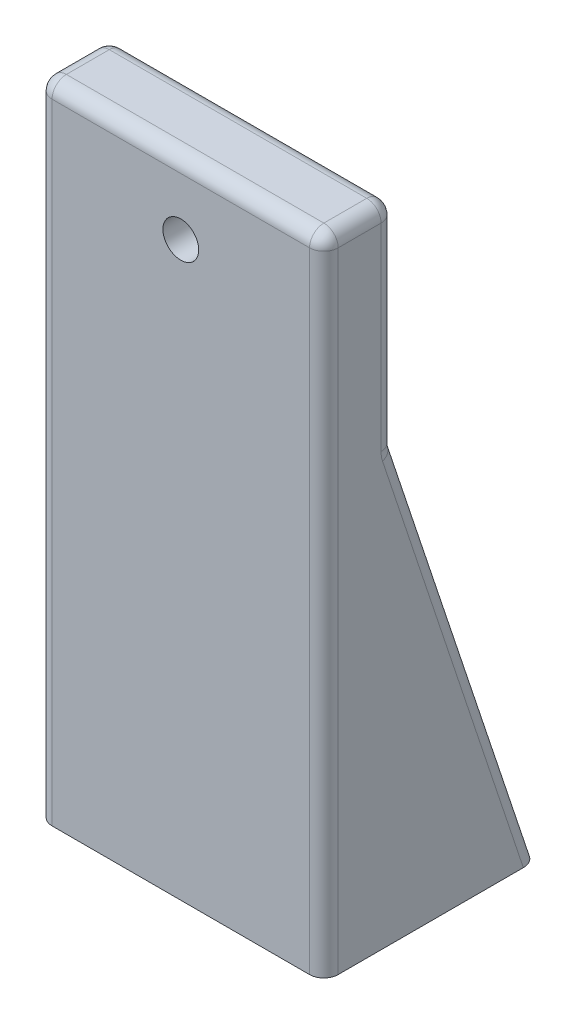
SolidWorks part; units mm, degrees
material "PLA"
ref_plane "Front Plane" through (0, 0, 0) normal (0, 0, 1) x (1, 0, 0)
ref_plane "Top Plane" through (0, 0, 0) normal (0, 1, 0) x (1, 0, 0)
ref_plane "Right Plane" through (0, 0, 0) normal (1, 0, 0) x (0, 0, -1)
sketch "Sketch1" plane through (0, 0, 0) normal (0, 0, 1) x (1, 0, 0)
  line L1 (-25.4, -57.15) -> (25.4, -57.15)
  line L2 (-25.4, -57.15) -> (-25.4, 57.15)
  line L3 (-25.4, 57.15) -> (25.4, 57.15)
  line L4 (25.4, -57.15) -> (25.4, 57.15)
  line L5 (-25.4, -57.15) -> (25.4, 57.15) construction
  line L6 (-25.4, 57.15) -> (25.4, -57.15) construction
  circle A0 centre (0, 44.45) radius 3.175
  point P0 (0, 0)
  point P8 (0, 0)
  dimension "D4" = 6.35
  dimension "D1" = 114.3
  dimension "D2" = 50.8
  dimension "D3" = 101.6
extrude "Boss-Extrude1" add sketch "Sketch1" along normal mid plane 12.7
sketch "Sketch3" plane through (25.4, 0, 0) normal (1, 0, 0) x (0, 0, -1)
  line L0 (6.35, -57.15) -> (31.75, -57.15)
  line L1 (31.75, -57.15) -> (6.35, 19.05)
  line L2 (6.35, -57.15) -> (6.35, 57.15) construction
  line L3 (6.35, 19.05) -> (6.35, -57.15)
  dimension "D1" = 25.4
  dimension "D2" = 76.2
extrude "Boss-Extrude2" add sketch "Sketch3" against normal through all
sketch "Sketch2" plane through (0, -57.15, 0) normal (0, -1, 0) x (1, 0, 0)
  line L0 (-15.24, 0) -> (15.24, 0) construction
  line L2 (-15.24, -22.86) -> (15.24, -22.86) construction
  line L3 (-15.24, -22.86) -> (-15.24, 0) construction
  line L4 (-15.24, 0) -> (15.24, 0) construction
  line L5 (15.24, -22.86) -> (15.24, 0) construction
  line L6 (-15.24, -22.86) -> (15.24, 0) construction
  line L7 (-15.24, 0) -> (15.24, -22.86) construction
  circle A0 centre (-15.24, 0) radius 1.5
  circle A1 centre (15.24, 0) radius 1.5
  circle A2 centre (-15.24, -22.86) radius 1.5
  circle A3 centre (15.24, -22.86) radius 1.5
  point P4 (0, 0)
  point P5 (0, -11.43)
  dimension "D1" = 3
  dimension "D2" = 30.48
  dimension "D3" = 22.86
extrude "Cut-Extrude1" cut sketch "Sketch2" against normal blind 12.7
fillet "Fillet1" radius 2.54 11 edges at (-25.4, -19.05, -19.05) (25.4, -19.05, -19.05) (-25.4, 0, 6.35) (-25.4, 57.15, 0) (25.4, 57.15, 0) (0, 57.15, 6.35) (25.4, 0, 6.35) (-25.4, 38.1, -6.35) (0, 57.15, -6.35) (25.4, 38.1, -6.35) (0, 19.05, -6.35)
